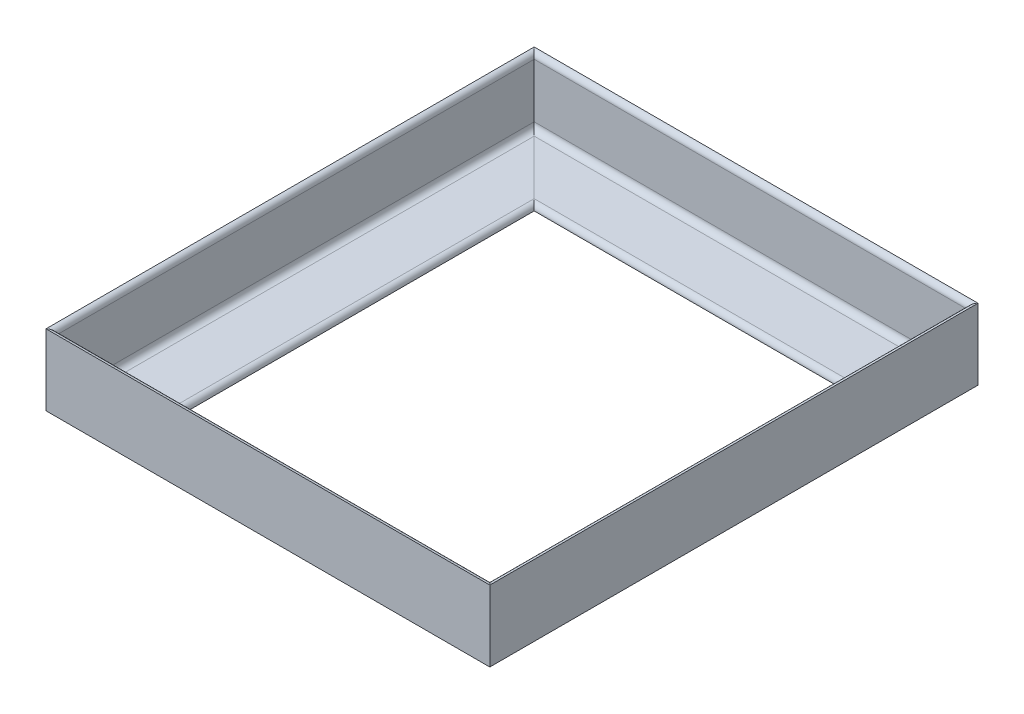
SolidWorks part; units mm, degrees
ref_plane "Front Plane" through (0, 0, 0) normal (0, 0, 1) x (1, 0, 0)
ref_plane "Top Plane" through (0, 0, 0) normal (0, 1, 0) x (1, 0, 0)
ref_plane "Right Plane" through (0, 0, 0) normal (1, 0, 0) x (0, 0, -1)
sketch3d "3DSketch1"
  line L1 (125, 0, 137.5) -> (125, 0, -137.5)
  line L2 (125, 0, 137.5) -> (-125, 0, 137.5)
  line L3 (-125, 0, 137.5) -> (-125, 0, -137.5)
  line L4 (125, 0, -137.5) -> (-125, 0, -137.5)
  line L5 (125, 0, 137.5) -> (-125, 0, -137.5) construction
  line L6 (-125, 0, 137.5) -> (125, 0, -137.5) construction
  point P0 (0, 0, 0)
  dimension "D1" = 275
  dimension "D2" = 250
other "Iron V40X40X3(1)"
ref_plane "Plane1" through (-125, 0, 137.5) normal (0, 0, -1) x (0, 1, 0)
sketch "Sketch11" plane through (-125, 0, 137.5) normal (0, 0, -1) x (0, 1, 0)
  line L0 (0, 0) -> (0, 40)
  line L1 (0, 20) -> (3, 20) construction
  line L2 (3, 37) -> (3, 6.5)
  line L3 (6.5, 3) -> (37, 3)
  line L4 (20, 3) -> (20, 0) construction
  line L5 (40, 0) -> (0, 0)
  arc A0 (40, 0) -> (37, 3) centre (37, 0) ccw
  arc A1 (0, 40) -> (3, 37) centre (0, 37) cw
  arc A2 (6.5, 3) -> (3, 6.5) centre (6.5, 6.5) cw
  point P10 (20, 0)
  point P14 (0, 20)
  point P15 (3, 20)
  point P16 (20, 3)
  point P17 (3, 40)
  point P18 (40, 3)
  point P21 (0, 0)
  dimension "D2" = 3
  dimension "D3" = 40
  dimension "Radius_1" = 3.5
  dimension "D1" = 3
